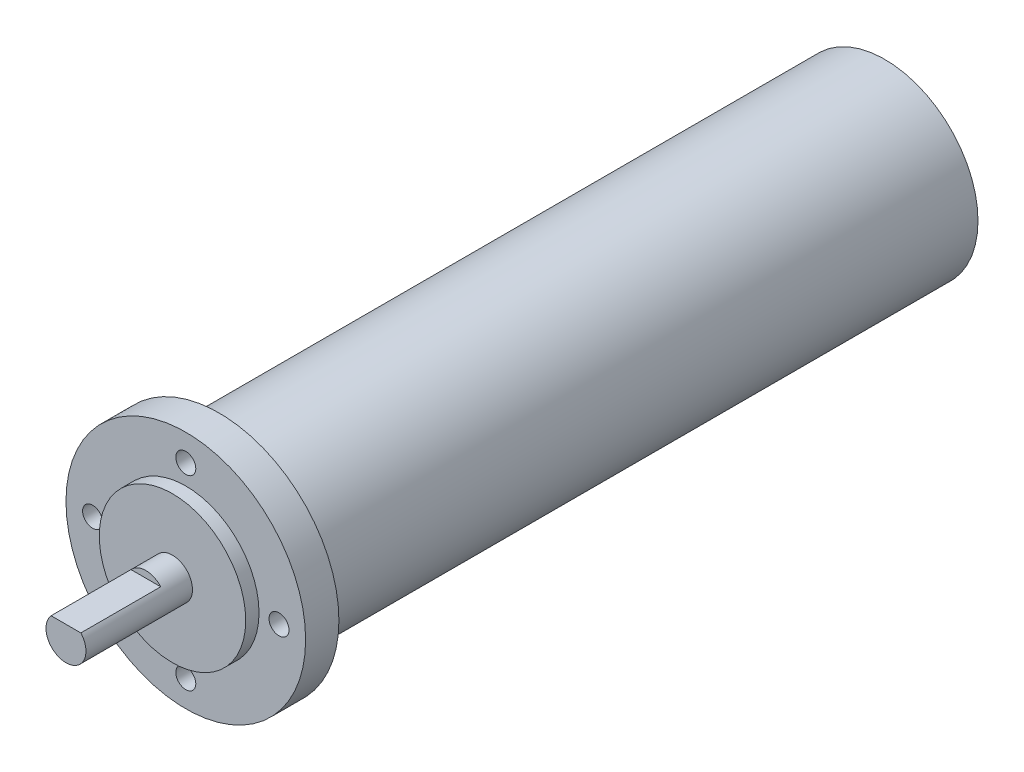
SolidWorks part; units mm, degrees
ref_plane "Front Plane" through (0, 0, 0) normal (0, 0, 1) x (1, 0, 0)
ref_plane "Top Plane" through (0, 0, 0) normal (0, 1, 0) x (1, 0, 0)
ref_plane "Right Plane" through (0, 0, 0) normal (1, 0, 0) x (0, 0, -1)
sketch "Sketch1" plane through (0, 0, 0) normal (0, 0, 1) x (1, 0, 0)
  circle A0 centre (0, 0) radius 14
  dimension "D1" = 28
extrude "Boss-Extrude3" add sketch "Sketch1" along normal blind 100 contours A0
sketch "Sketch4" plane through (0, 0, 100) normal (0, 0, 1) x (1, 0, 0)
  circle A0 centre (0, 0) radius 18
  dimension "D1" = 36
extrude "Boss-Extrude4" add sketch "Sketch4" along normal blind 5
sketch "Sketch5" plane through (0, 0, 105) normal (0, 0, 1) x (1, 0, 0)
  circle A0 centre (0, 0) radius 14 construction
  circle A1 centre (0, 14) radius 1.5
  circle A2 centre (14, 0) radius 1.5
  circle A3 centre (0, -14) radius 1.5
  circle A4 centre (-14, 0) radius 1.5
  dimension "D1" = 28
  dimension "D2" = 3
extrude "Cut-Extrude2" cut sketch "Sketch5" against normal blind 4
sketch "Sketch6" plane through (0, 0, 105) normal (0, 0, 1) x (1, 0, 0)
  circle A0 centre (0, 0) radius 11
  dimension "D1" = 22
extrude "Boss-Extrude6" add sketch "Sketch6" along normal blind 2 contours A0
sketch "Sketch7" plane through (0, 0, 107) normal (0, 0, 1) x (1, 0, 0)
  circle A0 centre (0, 0) radius 3
  dimension "D1" = 6
extrude "Boss-Extrude7" add sketch "Sketch7" along normal blind 16
sketch "Sketch8" plane through (0, 0, 0) normal (1, 0, 0) x (0, 0, -1)
  line L0 (-123, 3) -> (-123, -3) construction
  line L1 (-124.782, 9.151) -> (-111, 9.151)
  line L2 (-124.782, 9.151) -> (-124.782, 2)
  line L3 (-124.782, 2) -> (-111, 2)
  line L4 (-111, 9.151) -> (-111, 2)
  line L6 (19.8, 0) -> (-19.8, 0) construction
  dimension "D1" = 12
  dimension "D2" = 2
extrude "Cut-Extrude3" cut sketch "Sketch8" against normal mid plane 16
